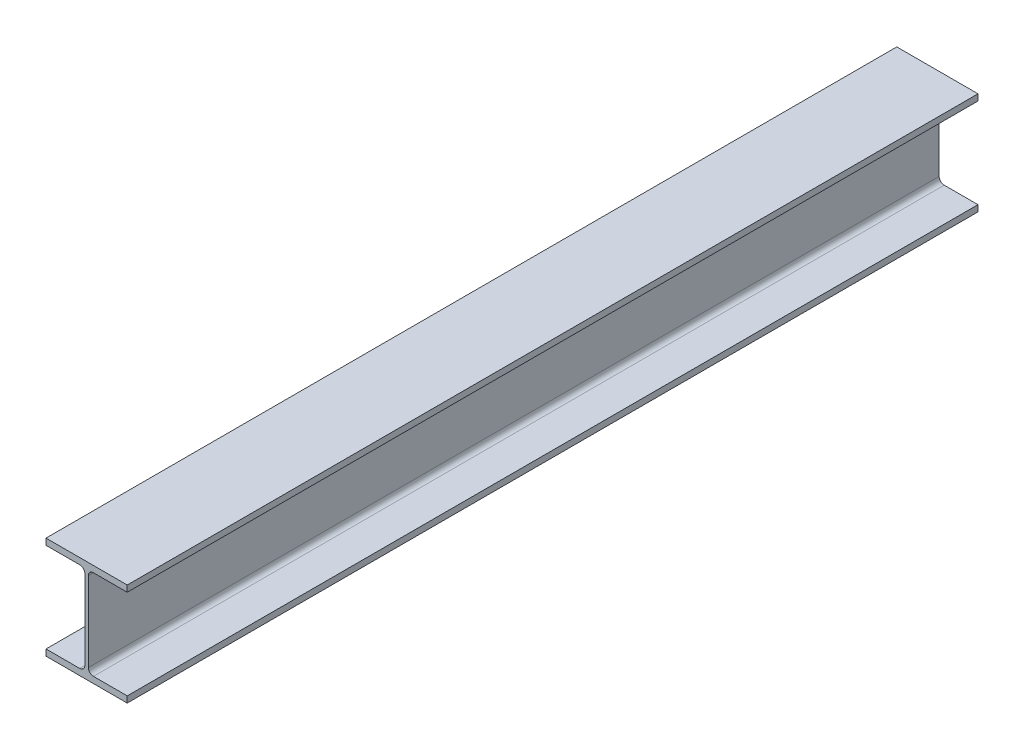
SolidWorks part; units mm, degrees
ref_plane "Plane1" through (0, 0, 0) normal (0, 0, 1) x (1, 0, 0)
ref_plane "Plane2" through (0, 0, 0) normal (0, 1, 0) x (1, 0, 0)
ref_plane "Plane3" through (0, 0, 0) normal (1, 0, 0) x (0, 0, -1)
sketch "Sketch1" plane through (0, 0, 0) normal (0, 0, 1) x (1, 0, 0)
  line L0 (0, 0) -> (0, 15.748)
  line L1 (0, 15.748) -> (84.709, 15.748)
  line L2 (97.409, 28.448) -> (97.409, 228.092)
  line L3 (84.709, 240.792) -> (0, 240.792)
  line L4 (0, 240.792) -> (0, 256.54)
  line L5 (0, 256.54) -> (203.708, 256.54)
  line L6 (203.708, 256.54) -> (203.708, 240.792)
  line L7 (203.708, 240.792) -> (118.999, 240.792)
  line L8 (106.299, 228.092) -> (106.299, 28.448)
  line L9 (118.999, 15.748) -> (203.708, 15.748)
  line L10 (203.708, 15.748) -> (203.708, 0)
  line L11 (203.708, 0) -> (0, 0)
  line L12 (101.854, -72.1361) -> (101.854, 256.54) construction
  arc A0 (84.709, 15.748) -> (97.409, 28.448) centre (84.709, 28.448) ccw
  arc A1 (97.409, 228.092) -> (84.709, 240.792) centre (84.709, 228.092) ccw
  arc A2 (118.999, 240.792) -> (106.299, 228.092) centre (118.999, 228.092) ccw
  arc A3 (106.299, 28.448) -> (118.999, 15.748) centre (118.999, 28.448) ccw
  dimension "Ri" = 12.7
  dimension "Tw" = 8.89
  dimension "Bf" = 203.708
  dimension "Depth" = 256.54
  dimension "Tf" = 15.748
  dimension "D2" = 15.748
  dimension "D1" = 4.445
extrude "BaseSteelW" add sketch "Sketch1" against normal mid plane 2133.6
equation "\"D1@Sketch1\" = \"Tw@Sketch1\" / 2"
equation "\"D2@Sketch1\" = \"Tf@Sketch1\""
